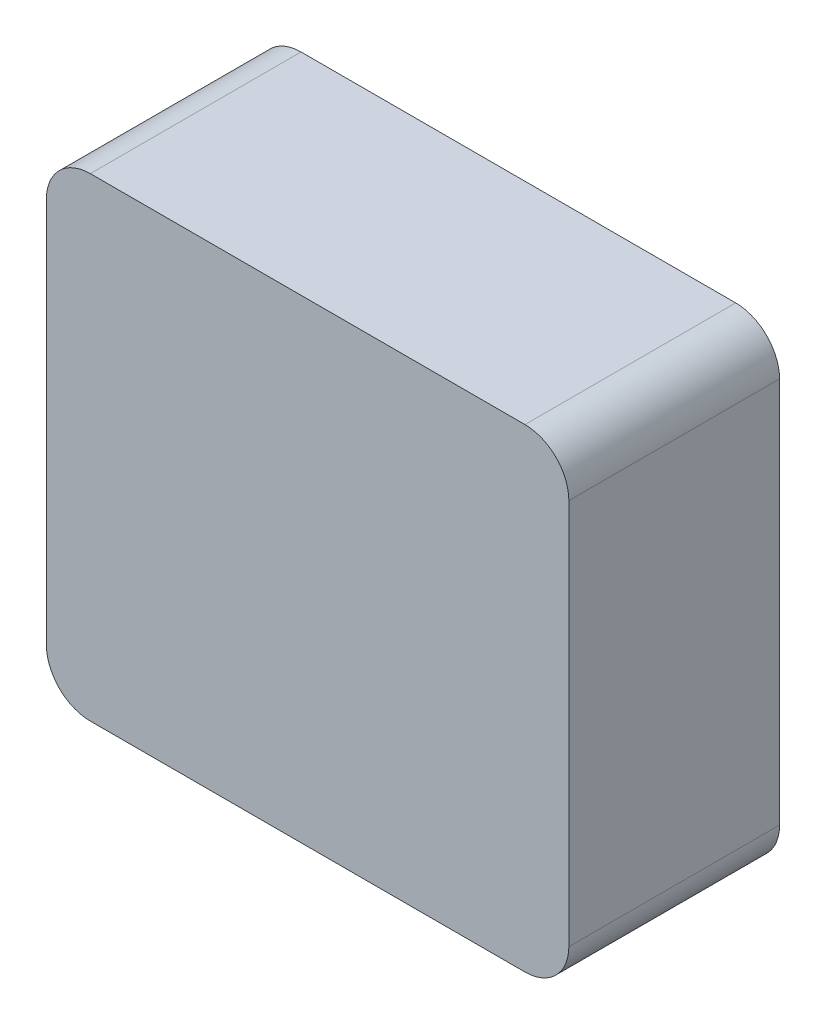
SolidWorks part; units mm, degrees
ref_plane "前视基准面" through (0, 0, 0) normal (0, 0, 1) x (1, 0, 0)
ref_plane "上视基准面" through (0, 0, 0) normal (0, 1, 0) x (1, 0, 0)
ref_plane "右视基准面" through (0, 0, 0) normal (1, 0, 0) x (0, 0, -1)
sketch "草图1" plane through (0, 0, 0) normal (0, 0, 1) x (1, 0, 0)
  line L1 (0, 0) -> (-238, 0)
  line L2 (0, 0) -> (0, -216)
  line L3 (0, -216) -> (-238, -216)
  line L4 (-238, 0) -> (-238, -216)
extrude "凸台-拉伸1" add sketch "草图1" along normal blind 96
fillet "圆角1" radius 20 4 edges at (-238, -216, 48) (-238, 0, 48) (0, -216, 48) (0, 0, 48)
